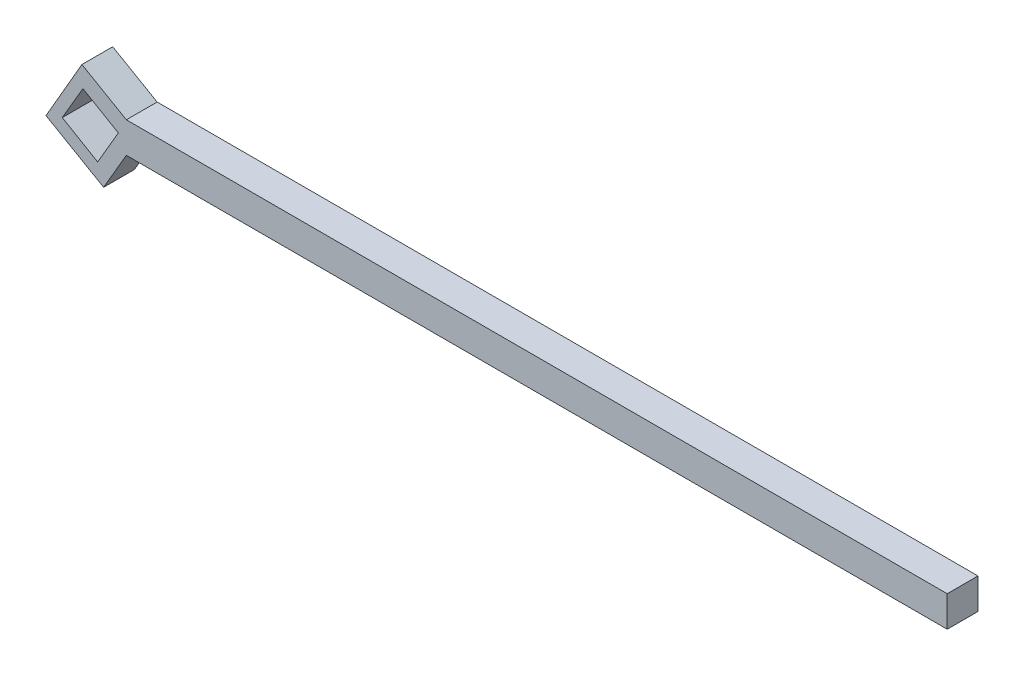
SolidWorks part; units mm, degrees
ref_plane "前视基准面" through (0, 0, 0) normal (0, 0, 1) x (1, 0, 0)
ref_plane "上视基准面" through (0, 0, 0) normal (0, 1, 0) x (1, 0, 0)
ref_plane "右视基准面" through (0, 0, 0) normal (1, 0, 0) x (0, 0, -1)
sketch "草图2" plane through (0, 0, 0) normal (0, 0, 1) x (1, 0, 0)
  line L1 (-359.8357, 15) -> (40.1643, 15)
  line L2 (40.1643, 15) -> (40.1643, 0)
  line L3 (40.1643, 0) -> (-359.8357, 0)
  line L8 (-373.7999, -9.7733) -> (-391.0732, 0.308)
  line L9 (-391.0732, 0.308) -> (-380.9919, 17.5813)
  line L10 (-380.9919, 17.5813) -> (-363.7186, 7.5)
  line L11 (-363.7186, 7.5) -> (-373.7999, -9.7733)
  line L12 (-363.7186, 7.5) -> (-359.8357, 7.5) construction
  line L13 (-359.8357, 15) -> (-381.4864, 27.5)
  line L14 (-381.4864, 27.5) -> (-398.9864, -2.8109)
  line L15 (-398.9864, -2.8109) -> (-370.8998, -19.0267)
  line L16 (-370.8998, -19.0267) -> (-359.8357, 0)
  dimension "D1" = 15
  dimension "D2" = 400
  dimension "D3" = 25
  dimension "D4" = 20
  dimension "D5" = 20
  dimension "D6" = 35
  dimension "D7" = 22.0097
extrude "凸台-拉伸2" add sketch "草图2" along normal blind 15
